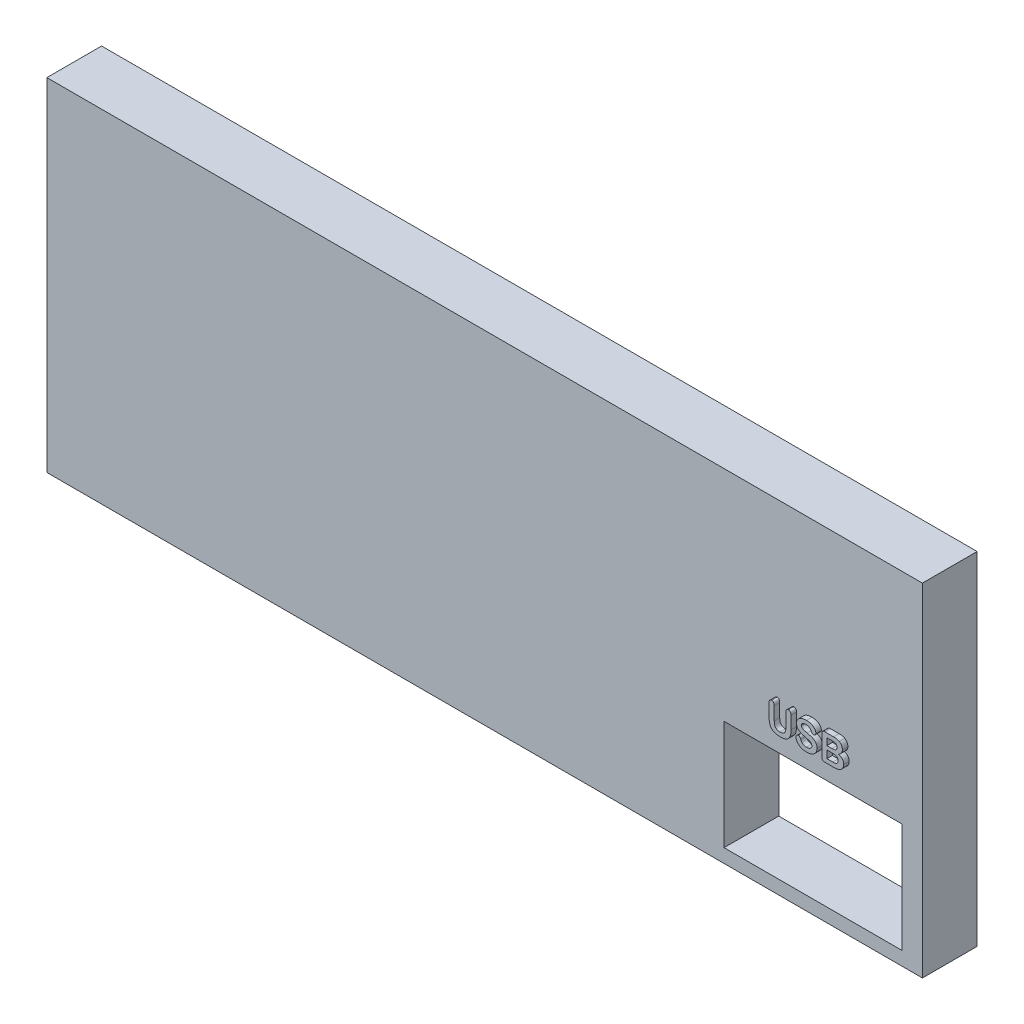
SolidWorks part; units mm, degrees
ref_plane "Front Plane" through (0, 0, 0) normal (0, 0, 1) x (1, 0, 0)
ref_plane "Top Plane" through (0, 0, 0) normal (0, 1, 0) x (1, 0, 0)
ref_plane "Right Plane" through (0, 0, 0) normal (1, 0, 0) x (0, 0, -1)
sketch "Sketch1" plane through (0, 0, 0) normal (0, 0, 1) x (1, 0, 0)
  line L1 (-25.5838, 14.7208) -> (38.4162, 14.7208)
  line L2 (-25.5838, 14.7208) -> (-25.5838, -10.2792)
  line L3 (-25.5838, -10.2792) -> (38.4162, -10.2792)
  line L4 (38.4162, 14.7208) -> (38.4162, -10.2792)
  dimension "D1" = 64
  dimension "D2" = 25
extrude "Boss-Extrude1" add sketch "Sketch1" along normal blind 4
sketch "Sketch2" plane through (0, 0, 0) normal (0, 0, -1) x (-1, 0, 0)
  line L0 (25.5838, 14.7208) -> (25.5838, -10.2792) construction
  line L1 (21.5838, -6.7792) -> (-18.4162, -6.7792)
  line L2 (21.5838, -6.7792) -> (21.5838, -7.7792)
  line L3 (21.5838, -7.7792) -> (-18.4162, -7.7792)
  line L4 (-18.4162, -6.7792) -> (-18.4162, -7.7792)
  line L5 (25.5838, -10.2792) -> (-38.4162, -10.2792) construction
  point P4 (21.5838, -7.2792)
  dimension "D1" = 40
  dimension "D2" = 1
  dimension "D3" = 4
  dimension "D4" = 2.5
extrude "Boss-Extrude2" add sketch "Sketch2" along normal blind 1.5
sketch "Sketch3" plane through (0, 0, 0) normal (0, 0, -1) x (-1, 0, 0)
  line L0 (25.5838, 14.7208) -> (25.5838, -10.2792) construction
  line L1 (-18.4162, -3.7792) -> (21.5838, -3.7792)
  line L2 (-18.4162, -3.7792) -> (-18.4162, -4.7792)
  line L3 (-18.4162, -4.7792) -> (21.5838, -4.7792)
  line L4 (21.5838, -3.7792) -> (21.5838, -4.7792)
  line L5 (21.5838, -6.7792) -> (-18.4162, -6.7792) construction
  dimension "D1" = 40
  dimension "D2" = 4
  dimension "D3" = 1
  dimension "D4" = 2
extrude "Boss-Extrude3" add sketch "Sketch3" along normal blind 1.5
sketch "Sketch4" plane through (0, 0, 4) normal (0, 0, 1) x (1, 0, 0)
  line L0 (38.4162, -10.2792) -> (38.4162, 14.7208) construction
  line L1 (23.9162, -1.2792) -> (36.9162, -1.2792)
  line L2 (23.9162, -1.2792) -> (23.9162, -9.2792)
  line L3 (23.9162, -9.2792) -> (36.9162, -9.2792)
  line L4 (36.9162, -1.2792) -> (36.9162, -9.2792)
  line L5 (-25.5838, -10.2792) -> (38.4162, -10.2792) construction
  dimension "D1" = 13
  dimension "D2" = 8
  dimension "D3" = 1.5
  dimension "D4" = 1
extrude "Cut-Extrude2" cut sketch "Sketch4" against normal blind 5.27
sketch "Sketch7" plane through (0, 0, 4) normal (0, 0, 1) x (1, 0, 0)
  text T0 "USB" font "Arial Rounded MT Bold" height 2
extrude "Boss-Extrude5" add sketch "Sketch7" along normal blind 0.4
